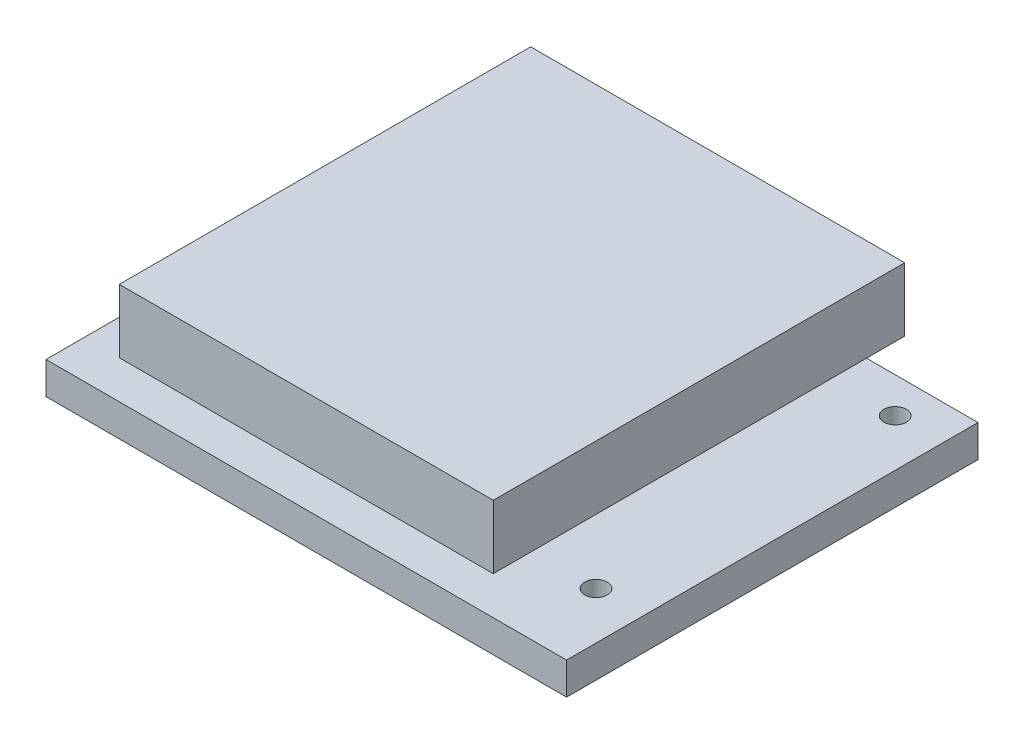
SolidWorks part; units mm, degrees
ref_plane "Front Plane" through (0, 0, 0) normal (0, 0, 1) x (1, 0, 0)
ref_plane "Top Plane" through (0, 0, 0) normal (0, 1, 0) x (1, 0, 0)
ref_plane "Right Plane" through (0, 0, 0) normal (1, 0, 0) x (0, 0, -1)
sketch "Sketch1" plane through (0, 0, 0) normal (0, 1, 0) x (1, 0, 0)
  line L0 (0, -30.085) -> (0, 30.085) construction
  line L1 (-34.8, -27.5) -> (34.8, -27.5)
  line L2 (-34.8, -27.5) -> (-34.8, 27.5)
  line L3 (-34.8, 27.5) -> (34.8, 27.5)
  line L4 (34.8, -27.5) -> (34.8, 27.5)
  line L5 (-34.8, -27.5) -> (34.8, 27.5) construction
  line L6 (-34.8, 27.5) -> (34.8, -27.5) construction
  circle A0 centre (28.4791, 22.75) radius 1.5
  circle A1 centre (28.4791, -17.25) radius 1.5
  circle A2 centre (-28.4791, -17.25) radius 1.5
  circle A3 centre (-28.4791, 22.75) radius 1.5
  point P0 (0, 0)
  point P8 (0, 0)
  point P9 (0, 0)
  point P12 (28.4791, 12.7875)
  dimension "D3" = 3
  dimension "D5" = 3
  dimension "D6" = 40
  dimension "D1" = 55
  dimension "D2" = 69.6
  dimension "D4" = 4.75
extrude "Boss-Extrude1" add sketch "Sketch1" along normal blind 4.3
ref_plane "Plane1" through (0, 9.4, 0) normal (0, 1, 0) x (1, 0, 0)
sketch "Sketch3" plane through (0, 9.4, 0) normal (0, 1, 0) x (1, 0, 0)
  line L0 (34.8, 27.5) -> (-34.8, 27.5) construction
  line L1 (-25, -27.5) -> (25, -27.5)
  line L2 (-25, -27.5) -> (-25, 27.5)
  line L3 (-25, 27.5) -> (25, 27.5)
  line L4 (25, -27.5) -> (25, 27.5)
  line L5 (-25, -27.5) -> (25, 27.5) construction
  line L6 (-25, 27.5) -> (25, -27.5) construction
  point P0 (0, 0)
  dimension "D1" = 50
extrude "Boss-Extrude2" add sketch "Sketch3" along normal blind 1.5 separate body contours L3 L4 L1 L2
sketch "Sketch5" plane through (0, 10.9, 0) normal (0, 1, 0) x (1, 0, 0)
  line L1 (-25, -27.5) -> (25, -27.5)
  line L2 (-25, -27.5) -> (-25, 27.5)
  line L3 (-25, 27.5) -> (25, 27.5)
  line L4 (25, -27.5) -> (25, 27.5)
  line L5 (-25, -27.5) -> (25, 27.5) construction
  line L6 (-25, 27.5) -> (25, -27.5) construction
  point P0 (0, 0)
extrude "Boss-Extrude3" add sketch "Sketch5" along normal blind 7
